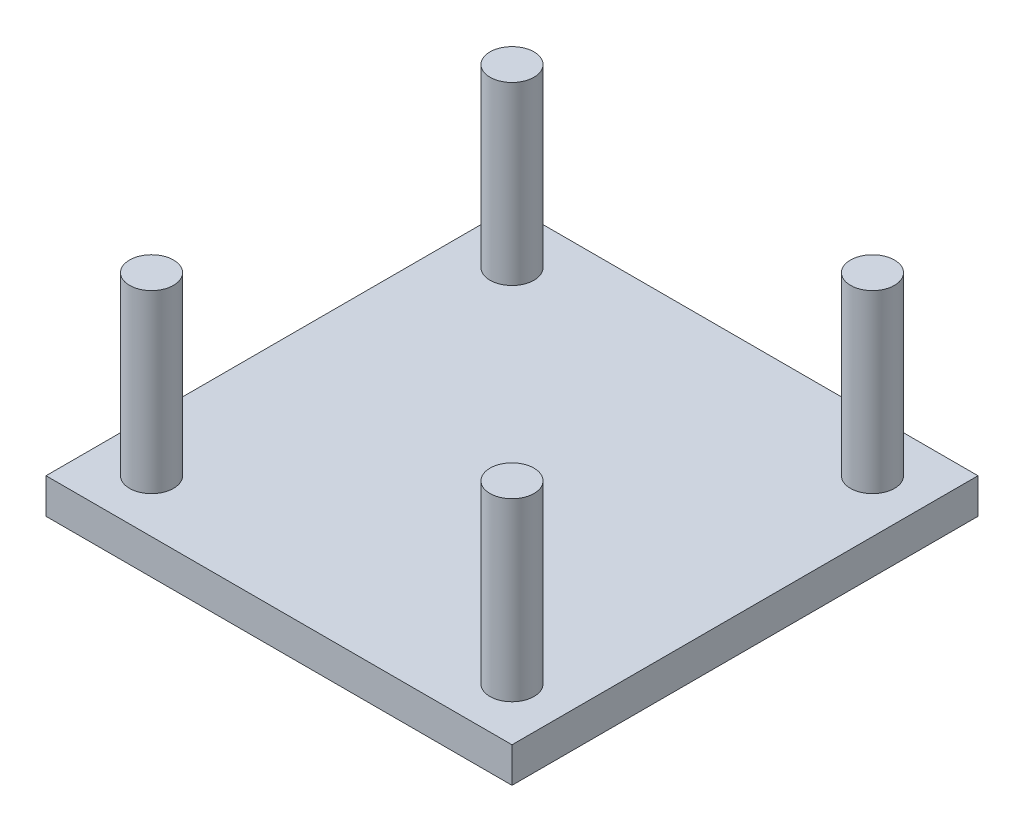
SolidWorks part; units mm, degrees
ref_plane "Front Plane" through (0, 0, 0) normal (0, 0, 1) x (1, 0, 0)
ref_plane "Top Plane" through (0, 0, 0) normal (0, 1, 0) x (1, 0, 0)
ref_plane "Right Plane" through (0, 0, 0) normal (1, 0, 0) x (0, 0, -1)
sketch "Sketch1" plane through (0, 0, 0) normal (0, 1, 0) x (1, 0, 0)
  line L1 (-10.25, 10.25) -> (10.25, 10.25) construction
  line L2 (-10.25, 10.25) -> (-10.25, -10.25) construction
  line L3 (-10.25, -10.25) -> (10.25, -10.25) construction
  line L4 (10.25, 10.25) -> (10.25, -10.25) construction
  line L5 (-10.25, 10.25) -> (10.25, -10.25) construction
  line L6 (-10.25, -10.25) -> (10.25, 10.25) construction
  circle A0 centre (-10.25, -10.25) radius 1.25
  circle A1 centre (-10.25, 10.25) radius 1.25
  circle A2 centre (10.25, 10.25) radius 1.25
  circle A3 centre (10.25, -10.25) radius 1.25
  circle A4 centre (-10.25, 10.25) radius 2.25 construction
  circle A5 centre (10.25, 10.25) radius 2.25 construction
  circle A6 centre (10.25, -10.25) radius 2.25 construction
  circle A7 centre (-10.25, -10.25) radius 2.25 construction
  point P0 (0, 0)
  dimension "D3" = 2.5
  dimension "D4" = 4.5
  dimension "D1" = 20.5
  dimension "D2" = 20.5
extrude "Boss-Extrude1" add sketch "Sketch1" along normal blind 10
sketch "Sketch2" plane through (0, 0, 0) normal (0, -1, 0) x (1, 0, 0)
  line L1 (-10.25, 10.25) -> (10.25, 10.25) construction
  line L2 (-10.25, 10.25) -> (-10.25, -10.25) construction
  line L3 (-10.25, -10.25) -> (10.25, -10.25) construction
  line L4 (10.25, 10.25) -> (10.25, -10.25) construction
  line L5 (-13.25, 13.25) -> (13.25, 13.25)
  line L6 (-13.25, 13.25) -> (-13.25, -13.25)
  line L7 (-13.25, -13.25) -> (13.25, -13.25)
  line L8 (13.25, 13.25) -> (13.25, -13.25)
  line L9 (-13.25, 13.25) -> (13.25, -13.25) construction
  line L10 (-13.25, -13.25) -> (13.25, 13.25) construction
  point P6 (0, 0)
  dimension "D1" = 3
extrude "Boss-Extrude2" add sketch "Sketch2" along normal blind 2
sketch "Sketch3" plane through (0, -2, 0) normal (0, -1, 0) x (1, 0, 0)
  line L0 (-13.25, 13.25) -> (-13.25, -13.25) construction
  line L1 (-13.25, -13.25) -> (13.25, -13.25) construction
  circle A0 centre (-4, -10.25) radius 1
  circle A1 centre (4, -10.25) radius 1
  point P8 (0, 0)
  point P9 (0, 0)
  point P10 (0, 0)
  dimension "D1" = 8
  dimension "D2" = 9.25
  dimension "D3" = 3
  dimension "D4" = 2
extrude "Cut-Extrude1" cut sketch "Sketch3" against normal blind 1.5
